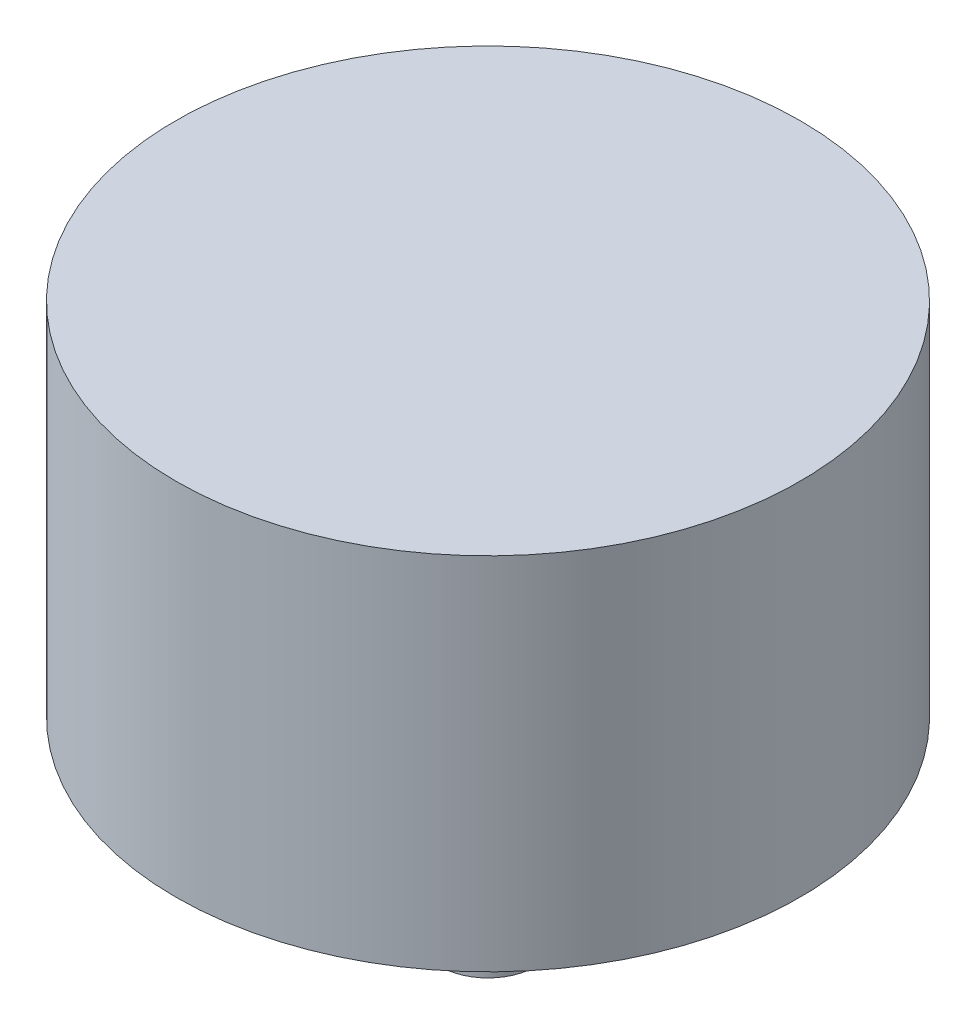
SolidWorks part; units mm, degrees
ref_plane "Front Plane" through (0, 0, 0) normal (0, 0, 1) x (1, 0, 0)
ref_plane "Top Plane" through (0, 0, 0) normal (0, 1, 0) x (1, 0, 0)
ref_plane "Right Plane" through (0, 0, 0) normal (1, 0, 0) x (0, 0, -1)
sketch "Sketch1" plane through (0, 0, 0) normal (0, 1, 0) x (1, 0, 0)
  circle A0 centre (0, 0) radius 650
extrude "Boss-Extrude1" add sketch "Sketch1" along normal blind 750
sketch "Sketch3" plane through (0, 0, 0) normal (0, -1, 0) x (1, 0, 0)
  circle A0 centre (0, 0) radius 100
extrude "Boss-Extrude2" add sketch "Sketch3" along normal blind 400
